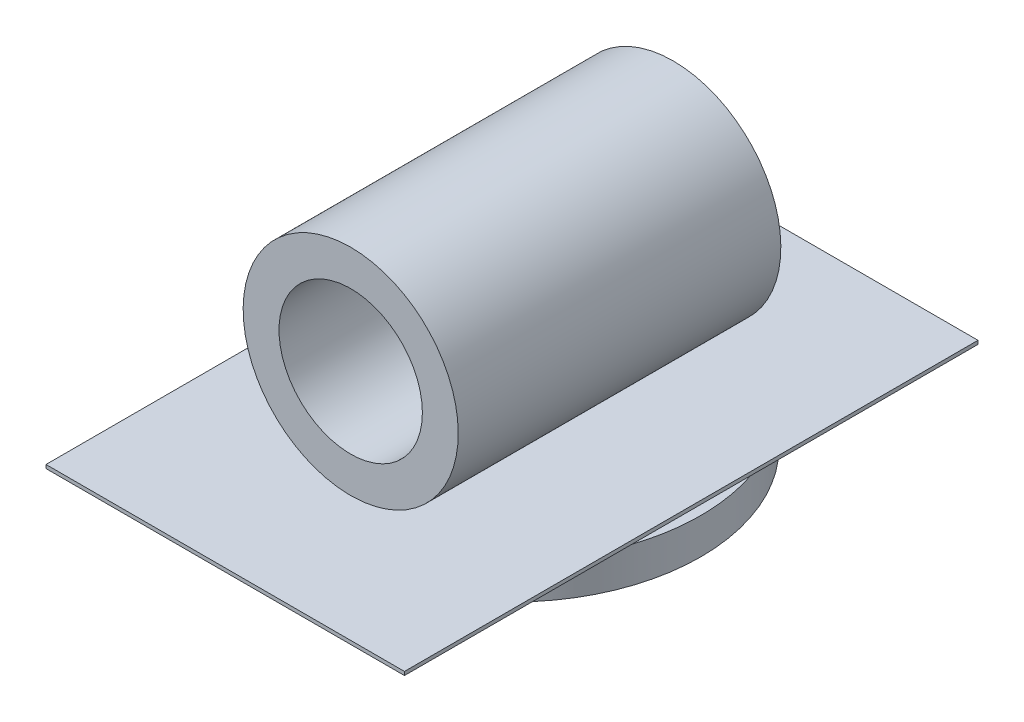
SolidWorks part; units mm, degrees
ref_plane "Front Plane" through (0, 0, 0) normal (0, 0, 1) x (1, 0, 0)
ref_plane "Top Plane" through (0, 0, 0) normal (0, 1, 0) x (1, 0, 0)
ref_plane "Right Plane" through (0, 0, 0) normal (1, 0, 0) x (0, 0, -1)
sketch "Sketch1" plane through (0, 0, 0) normal (0, 1, 0) x (1, 0, 0)
  line L1 (25, -40) -> (-25, -40)
  line L2 (25, -40) -> (25, 40)
  line L3 (25, 40) -> (-25, 40)
  line L4 (-25, -40) -> (-25, 40)
  line L5 (25, -40) -> (-25, 40) construction
  line L6 (25, 40) -> (-25, -40) construction
  point P0 (0, 0)
extrude "Boss-Extrude1" add sketch "Sketch1" along normal blind 0.5 contours L4 L3 L2 L1
sketch "Sketch4" plane through (0, 0, 0) normal (0, -1, 0) x (1, 0, 0)
  circle A0 centre (0, 0) radius 26.3356
extrude "Boss-Extrude2" add sketch "Sketch4" along normal blind 5
sketch "Sketch5" plane through (0, 0, 0) normal (0, 0, 1) x (1, 0, 0)
  line L0 (0, 0.5) -> (0, 15.4951) construction
  line L1 (25, 0.5) -> (-25, 0.5) construction
  line L2 (0, -55) -> (0, 55) construction
  circle A0 centre (0, 15.4951) radius 15
  point P8 (0, 18.3413)
  point P9 (0, 15.4951)
  dimension "D1" = 30
extrude "Boss-Extrude3" add sketch "Sketch5" along normal mid plane 45 contours A0
sketch "Sketch6" plane through (0, 0, 22.5) normal (0, 0, 1) x (1, 0, 0)
  line L0 (0, 0.5) -> (0, 40.7371) construction
  line L1 (0.384, 0.5) -> (-0.384, 0.5) construction
  line L2 (15, 15.4951) -> (-15, 15.4951) construction
  circle A0 centre (0, 15.4951) radius 15 construction
sketch "Sketch7" plane through (0, 0, 22.5) normal (0, 0, 1) x (1, 0, 0)
  circle A0 centre (0, 15.4983) radius 10
  point P2 (0, 15.4983)
extrude "Cut-Extrude2" cut sketch "Sketch7" against normal through all contours A0
